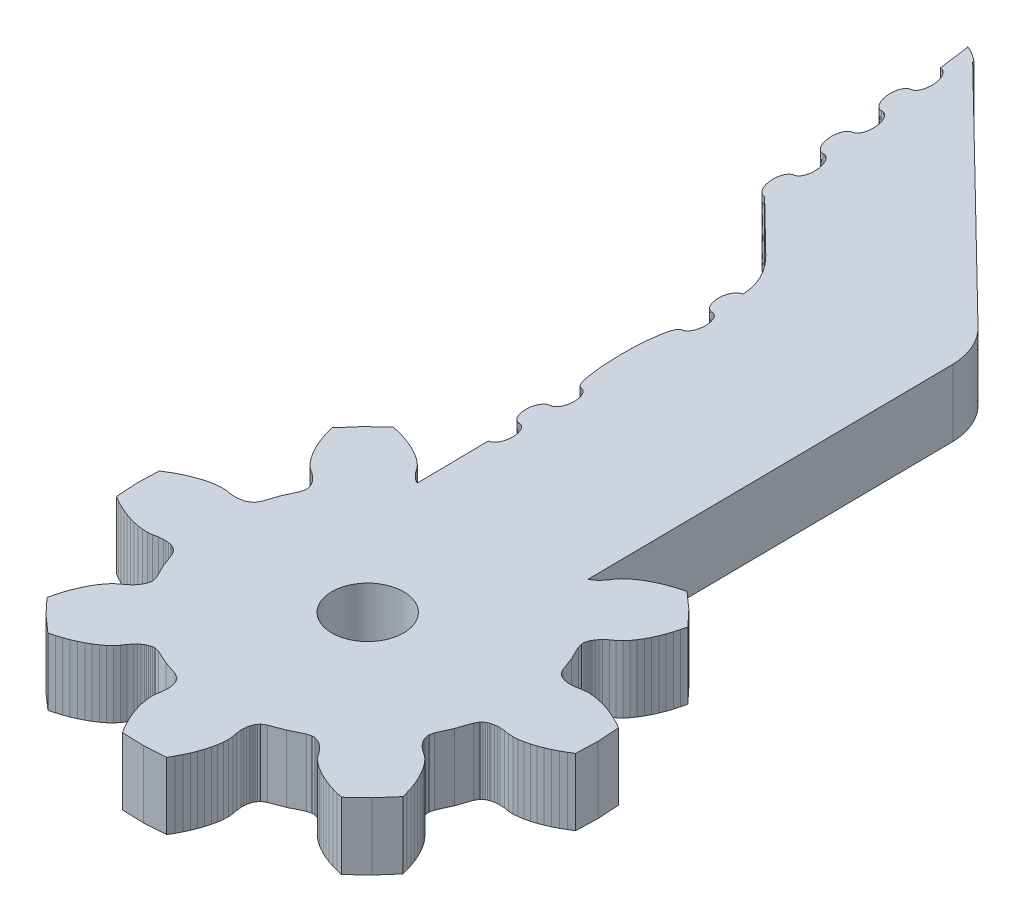
SolidWorks part; units mm, degrees
material "Acrylic (Medium-high impact)"
ref_plane "Front Plane" through (0, 0, 0) normal (0, 0, 1) x (1, 0, 0)
ref_plane "Top Plane" through (0, 0, 0) normal (0, 1, 0) x (1, 0, 0)
ref_plane "Right Plane" through (0, 0, 0) normal (1, 0, 0) x (0, 0, -1)
sketch "Sketch1" plane through (0, 0, 0) normal (0, 1, 0) x (1, 0, 0)
  line L0 (-18.2398, 12.6602) -> (-18.2057, 12.6938)
  line L1 (-18.2057, 12.6938) -> (-18.2497, 16.0706)
  line L2 (-19.267, 30.237) -> (-21.7416, 32.6549)
  line L3 (-22.8499, 42.0906) -> (-23.052, 43.5951)
  line L4 (-23.052, 43.5951) -> (-23.0777, 43.592)
  line L5 (-22.3058, 43.1423) -> (-22.3211, 43.0991)
  line L6 (-22.3211, 43.0991) -> (-11.3066, 32.3367)
  line L7 (-11.3066, 32.3367) -> (-11.3052, 32.3332)
  line L8 (-10.3897, 30.2281) -> (-10.2078, 12.7419)
  line L9 (-10.2078, 12.7419) -> (-10.1981, 12.7564)
  line L10 (-10.1981, 12.7564) -> (-10.1398, 12.7878)
  line L11 (-10.1398, 12.7878) -> (-10.0349, 12.8576)
  line L12 (-10.0349, 12.8576) -> (-9.9419, 12.9344)
  line L13 (-9.9419, 12.9344) -> (-9.858, 13.0164)
  line L14 (-9.858, 13.0164) -> (-9.7113, 13.1935)
  line L15 (-9.7113, 13.1935) -> (-9.5873, 13.3847)
  line L16 (-9.5873, 13.3847) -> (-9.4418, 13.5625)
  line L17 (-9.4418, 13.5625) -> (-9.2671, 13.7214)
  line L18 (-9.2671, 13.7214) -> (-9.0742, 13.868)
  line L19 (-9.0742, 13.868) -> (-8.8661, 14.0037)
  line L20 (-8.8661, 14.0037) -> (-8.6445, 14.1287)
  line L21 (-8.6445, 14.1287) -> (-8.4106, 14.2438)
  line L22 (-8.4106, 14.2438) -> (-8.1654, 14.3483)
  line L23 (-8.1654, 14.3483) -> (-7.9097, 14.4428)
  line L24 (-7.9097, 14.4428) -> (-7.6438, 14.5266)
  line L25 (-7.6438, 14.5266) -> (-7.3688, 14.6001)
  line L26 (-7.3688, 14.6001) -> (-6.5944, 13.9172)
  line L27 (-6.5944, 13.9172) -> (-5.8888, 13.1634)
  line L28 (-5.8888, 13.1634) -> (-5.9533, 12.8854)
  line L29 (-5.9533, 12.8854) -> (-6.0288, 12.6167)
  line L30 (-6.0288, 12.6167) -> (-6.115, 12.3576)
  line L31 (-6.115, 12.3576) -> (-6.2117, 12.1089)
  line L32 (-6.2117, 12.1089) -> (-6.3189, 11.8711)
  line L33 (-6.3189, 11.8711) -> (-6.4368, 11.6453)
  line L34 (-6.4368, 11.6453) -> (-6.5656, 11.4327)
  line L35 (-6.5656, 11.4327) -> (-6.7058, 11.2349)
  line L36 (-6.7058, 11.2349) -> (-6.859, 11.0549)
  line L37 (-6.859, 11.0549) -> (-7.0316, 10.9036)
  line L38 (-7.0316, 10.9036) -> (-7.2185, 10.7734)
  line L39 (-7.2185, 10.7734) -> (-7.3905, 10.621)
  line L40 (-7.3905, 10.621) -> (-7.47, 10.5345)
  line L41 (-7.47, 10.5345) -> (-7.5435, 10.4388)
  line L42 (-7.5435, 10.4388) -> (-7.6098, 10.3316)
  line L43 (-7.6098, 10.3316) -> (-7.6395, 10.2723)
  line L44 (-7.6395, 10.2723) -> (-7.6659, 10.2075)
  line L45 (-7.6659, 10.2075) -> (-7.6884, 10.1356)
  line L46 (-7.6884, 10.1356) -> (-7.7045, 10.0529)
  line L47 (-7.7045, 10.0529) -> (-7.7093, 9.95)
  line L48 (-7.7093, 9.95) -> (-7.6495, 9.7304)
  line L49 (-7.6495, 9.7304) -> (-7.3391, 9.0968)
  line L50 (-7.3391, 9.0968) -> (-7.0906, 8.4366)
  line L51 (-7.0906, 8.4366) -> (-6.9716, 8.2425)
  line L52 (-6.9716, 8.2425) -> (-6.8934, 8.1755)
  line L53 (-6.8934, 8.1755) -> (-6.8222, 8.1306)
  line L54 (-6.8222, 8.1306) -> (-6.7546, 8.0978)
  line L55 (-6.7546, 8.0978) -> (-6.6895, 8.0728)
  line L56 (-6.6895, 8.0728) -> (-6.6259, 8.0539)
  line L57 (-6.6259, 8.0539) -> (-6.5024, 8.0289)
  line L58 (-6.5024, 8.0289) -> (-6.3825, 8.0173)
  line L59 (-6.3825, 8.0173) -> (-6.2653, 8.0158)
  line L60 (-6.2653, 8.0158) -> (-6.0366, 8.0373)
  line L61 (-6.0366, 8.0373) -> (-5.8138, 8.0846)
  line L62 (-5.8138, 8.0846) -> (-5.5857, 8.1071)
  line L63 (-5.5857, 8.1071) -> (-5.3499, 8.0958)
  line L64 (-5.3499, 8.0958) -> (-5.1099, 8.0628)
  line L65 (-5.1099, 8.0628) -> (-4.867, 8.0111)
  line L66 (-4.867, 8.0111) -> (-4.622, 7.9427)
  line L67 (-4.622, 7.9427) -> (-4.3757, 7.8584)
  line L68 (-4.3757, 7.8584) -> (-4.1283, 7.7586)
  line L69 (-4.1283, 7.7586) -> (-3.8809, 7.6443)
  line L70 (-3.8809, 7.6443) -> (-3.6337, 7.5152)
  line L71 (-3.6337, 7.5152) -> (-3.3873, 7.3723)
  line L72 (-3.3873, 7.3723) -> (-3.3217, 6.3409)
  line L73 (-3.3217, 6.3409) -> (-3.355, 5.308)
  line L74 (-3.355, 5.308) -> (-3.5968, 5.1572)
  line L75 (-3.5968, 5.1572) -> (-3.8398, 5.0206)
  line L76 (-3.8398, 5.0206) -> (-4.0836, 4.8983)
  line L77 (-4.0836, 4.8983) -> (-4.3275, 4.7911)
  line L78 (-4.3275, 4.7911) -> (-4.5711, 4.6989)
  line L79 (-4.5711, 4.6989) -> (-4.814, 4.6227)
  line L80 (-4.814, 4.6227) -> (-5.055, 4.5635)
  line L81 (-5.055, 4.5635) -> (-5.2937, 4.523)
  line L82 (-5.2937, 4.523) -> (-5.5291, 4.5043)
  line L83 (-5.5291, 4.5043) -> (-5.758, 4.5197)
  line L84 (-5.758, 4.5197) -> (-5.9821, 4.56)
  line L85 (-5.9821, 4.56) -> (-6.2113, 4.5741)
  line L86 (-6.2113, 4.5741) -> (-6.3285, 4.569)
  line L87 (-6.3285, 4.569) -> (-6.4478, 4.5536)
  line L88 (-6.4478, 4.5536) -> (-6.5705, 4.5248)
  line L89 (-6.5705, 4.5248) -> (-6.6335, 4.5039)
  line L90 (-6.6335, 4.5039) -> (-6.698, 4.4769)
  line L91 (-6.698, 4.4769) -> (-6.7644, 4.4418)
  line L92 (-6.7644, 4.4418) -> (-6.8344, 4.3946)
  line L93 (-6.8344, 4.3946) -> (-6.9102, 4.3254)
  line L94 (-6.9102, 4.3254) -> (-7.023, 4.1278)
  line L95 (-7.023, 4.1278) -> (-7.2507, 3.4599)
  line L96 (-7.2507, 3.4599) -> (-7.5412, 2.8169)
  line L97 (-7.5412, 2.8169) -> (-7.5939, 2.5954)
  line L98 (-7.5939, 2.5954) -> (-7.5859, 2.4927)
  line L99 (-7.5859, 2.4927) -> (-7.5671, 2.4106)
  line L100 (-7.5671, 2.4106) -> (-7.5426, 2.3395)
  line L101 (-7.5426, 2.3395) -> (-7.514, 2.2756)
  line L102 (-7.514, 2.2756) -> (-7.4827, 2.2171)
  line L103 (-7.4827, 2.2171) -> (-7.4129, 2.1121)
  line L104 (-7.4129, 2.1121) -> (-7.3363, 2.0189)
  line L105 (-7.3363, 2.0189) -> (-7.2545, 1.9348)
  line L106 (-7.2545, 1.9348) -> (-7.0776, 1.7879)
  line L107 (-7.0776, 1.7879) -> (-6.8867, 1.6636)
  line L108 (-6.8867, 1.6636) -> (-6.7092, 1.5177)
  line L109 (-6.7092, 1.5177) -> (-6.5508, 1.3428)
  line L110 (-6.5508, 1.3428) -> (-6.4044, 1.1494)
  line L111 (-6.4044, 1.1494) -> (-6.269, 0.941)
  line L112 (-6.269, 0.941) -> (-6.1442, 0.7191)
  line L113 (-6.1442, 0.7191) -> (-6.0294, 0.4849)
  line L114 (-6.0294, 0.4849) -> (-5.9248, 0.2392)
  line L115 (-5.9248, 0.2392) -> (-5.8307, -0.017)
  line L116 (-5.8307, -0.017) -> (-5.7469, -0.2833)
  line L117 (-5.7469, -0.2833) -> (-5.6736, -0.5589)
  line L118 (-5.6736, -0.5589) -> (-6.3551, -1.3347)
  line L119 (-6.3551, -1.3347) -> (-7.1078, -2.0416)
  line L120 (-7.1078, -2.0416) -> (-7.3851, -1.9769)
  line L121 (-7.3851, -1.9769) -> (-7.6535, -1.9013)
  line L122 (-7.6535, -1.9013) -> (-7.9121, -1.8151)
  line L123 (-7.9121, -1.8151) -> (-8.1604, -1.718)
  line L124 (-8.1604, -1.718) -> (-8.3976, -1.6106)
  line L125 (-8.3976, -1.6106) -> (-8.6231, -1.4926)
  line L126 (-8.6231, -1.4926) -> (-8.8354, -1.3636)
  line L127 (-8.8354, -1.3636) -> (-9.0327, -1.2232)
  line L128 (-9.0327, -1.2232) -> (-9.2124, -1.0698)
  line L129 (-9.2124, -1.0698) -> (-9.3634, -0.8967)
  line L130 (-9.3634, -0.8967) -> (-9.4933, -0.7095)
  line L131 (-9.4933, -0.7095) -> (-9.6454, -0.5372)
  line L132 (-9.6454, -0.5372) -> (-9.732, -0.4577)
  line L133 (-9.732, -0.4577) -> (-9.8272, -0.384)
  line L134 (-9.8272, -0.384) -> (-9.9344, -0.3174)
  line L135 (-9.9344, -0.3174) -> (-9.9937, -0.2877)
  line L136 (-9.9937, -0.2877) -> (-10.0583, -0.2612)
  line L137 (-10.0583, -0.2612) -> (-10.13, -0.2389)
  line L138 (-10.13, -0.2389) -> (-10.2126, -0.2227)
  line L139 (-10.2126, -0.2227) -> (-10.3151, -0.2178)
  line L140 (-10.3151, -0.2178) -> (-10.5344, -0.2777)
  line L141 (-10.5344, -0.2777) -> (-11.1668, -0.5889)
  line L142 (-11.1668, -0.5889) -> (-11.826, -0.8376)
  line L143 (-11.826, -0.8376) -> (-12.0198, -0.9568)
  line L144 (-12.0198, -0.9568) -> (-12.0866, -1.0352)
  line L145 (-12.0866, -1.0352) -> (-12.1314, -1.1065)
  line L146 (-12.1314, -1.1065) -> (-12.1642, -1.1741)
  line L147 (-12.1642, -1.1741) -> (-12.189, -1.2395)
  line L148 (-12.189, -1.2395) -> (-12.208, -1.3032)
  line L149 (-12.208, -1.3032) -> (-12.233, -1.4269)
  line L150 (-12.233, -1.4269) -> (-12.2446, -1.547)
  line L151 (-12.2446, -1.547) -> (-12.246, -1.6643)
  line L152 (-12.246, -1.6643) -> (-12.2247, -1.8937)
  line L153 (-12.2247, -1.8937) -> (-12.1774, -2.1167)
  line L154 (-12.1774, -2.1167) -> (-12.1548, -2.3455)
  line L155 (-12.1548, -2.3455) -> (-12.1661, -2.5817)
  line L156 (-12.1661, -2.5817) -> (-12.1991, -2.8219)
  line L157 (-12.1991, -2.8219) -> (-12.2505, -3.0652)
  line L158 (-12.2505, -3.0652) -> (-12.319, -3.3107)
  line L159 (-12.319, -3.3107) -> (-12.4032, -3.5574)
  line L160 (-12.4032, -3.5574) -> (-12.5026, -3.8052)
  line L161 (-12.5026, -3.8052) -> (-12.6169, -4.0532)
  line L162 (-12.6169, -4.0532) -> (-12.7455, -4.3008)
  line L163 (-12.7455, -4.3008) -> (-12.8884, -4.5477)
  line L164 (-12.8884, -4.5477) -> (-13.918, -4.6133)
  line L165 (-13.918, -4.6133) -> (-14.949, -4.5801)
  line L166 (-14.949, -4.5801) -> (-15.0994, -4.3379)
  line L167 (-15.0994, -4.3379) -> (-15.2359, -4.0945)
  line L168 (-15.2359, -4.0945) -> (-15.3577, -3.8502)
  line L169 (-15.3577, -3.8502) -> (-15.4649, -3.6057)
  line L170 (-15.4649, -3.6057) -> (-15.5569, -3.3616)
  line L171 (-15.5569, -3.3616) -> (-15.6328, -3.1185)
  line L172 (-15.6328, -3.1185) -> (-15.692, -2.8768)
  line L173 (-15.692, -2.8768) -> (-15.7324, -2.6377)
  line L174 (-15.7324, -2.6377) -> (-15.751, -2.4021)
  line L175 (-15.751, -2.4021) -> (-15.7358, -2.1727)
  line L176 (-15.7358, -2.1727) -> (-15.6955, -1.9483)
  line L177 (-15.6955, -1.9483) -> (-15.6815, -1.7184)
  line L178 (-15.6815, -1.7184) -> (-15.6866, -1.601)
  line L179 (-15.6866, -1.601) -> (-15.702, -1.4815)
  line L180 (-15.702, -1.4815) -> (-15.7306, -1.3587)
  line L181 (-15.7306, -1.3587) -> (-15.7516, -1.2956)
  line L182 (-15.7516, -1.2956) -> (-15.7786, -1.2311)
  line L183 (-15.7786, -1.2311) -> (-15.8135, -1.1643)
  line L184 (-15.8135, -1.1643) -> (-15.8604, -1.0945)
  line L185 (-15.8604, -1.0945) -> (-15.9296, -1.0183)
  line L186 (-15.9296, -1.0183) -> (-16.127, -0.9054)
  line L187 (-16.127, -0.9054) -> (-16.7936, -0.6772)
  line L188 (-16.7936, -0.6772) -> (-17.4355, -0.3862)
  line L189 (-17.4355, -0.3862) -> (-17.6566, -0.3334)
  line L190 (-17.6566, -0.3334) -> (-17.7591, -0.3414)
  line L191 (-17.7591, -0.3414) -> (-17.841, -0.3601)
  line L192 (-17.841, -0.3601) -> (-17.9121, -0.3849)
  line L193 (-17.9121, -0.3849) -> (-17.9757, -0.4134)
  line L194 (-17.9757, -0.4134) -> (-18.0342, -0.445)
  line L195 (-18.0342, -0.445) -> (-18.1391, -0.5148)
  line L196 (-18.1391, -0.5148) -> (-18.232, -0.5914)
  line L197 (-18.232, -0.5914) -> (-18.316, -0.6736)
  line L198 (-18.316, -0.6736) -> (-18.4627, -0.8507)
  line L199 (-18.4627, -0.8507) -> (-18.5867, -1.0419)
  line L200 (-18.5867, -1.0419) -> (-18.7322, -1.2195)
  line L201 (-18.7322, -1.2195) -> (-18.907, -1.3786)
  line L202 (-18.907, -1.3786) -> (-19.0998, -1.525)
  line L203 (-19.0998, -1.525) -> (-19.3079, -1.6608)
  line L204 (-19.3079, -1.6608) -> (-19.5296, -1.786)
  line L205 (-19.5296, -1.786) -> (-19.7634, -1.9008)
  line L206 (-19.7634, -1.9008) -> (-20.0084, -2.0055)
  line L207 (-20.0084, -2.0055) -> (-20.2643, -2.0998)
  line L208 (-20.2643, -2.0998) -> (-20.5302, -2.1838)
  line L209 (-20.5302, -2.1838) -> (-20.8053, -2.2573)
  line L210 (-20.8053, -2.2573) -> (-21.5796, -1.5744)
  line L211 (-21.5796, -1.5744) -> (-22.2852, -0.8205)
  line L212 (-22.2852, -0.8205) -> (-22.2207, -0.5426)
  line L213 (-22.2207, -0.5426) -> (-22.1452, -0.2737)
  line L214 (-22.1452, -0.2737) -> (-22.059, -0.0148)
  line L215 (-22.059, -0.0148) -> (-21.9623, 0.2341)
  line L216 (-21.9623, 0.2341) -> (-21.8551, 0.4718)
  line L217 (-21.8551, 0.4718) -> (-21.7372, 0.6977)
  line L218 (-21.7372, 0.6977) -> (-21.6084, 0.9103)
  line L219 (-21.6084, 0.9103) -> (-21.4683, 1.1081)
  line L220 (-21.4683, 1.1081) -> (-21.3152, 1.2881)
  line L221 (-21.3152, 1.2881) -> (-21.1423, 1.4392)
  line L222 (-21.1423, 1.4392) -> (-20.9556, 1.5694)
  line L223 (-20.9556, 1.5694) -> (-20.7834, 1.7218)
  line L224 (-20.7834, 1.7218) -> (-20.7042, 1.8085)
  line L225 (-20.7042, 1.8085) -> (-20.6305, 1.904)
  line L226 (-20.6305, 1.904) -> (-20.5642, 2.0112)
  line L227 (-20.5642, 2.0112) -> (-20.5345, 2.0706)
  line L228 (-20.5345, 2.0706) -> (-20.5081, 2.1353)
  line L229 (-20.5081, 2.1353) -> (-20.4856, 2.2072)
  line L230 (-20.4856, 2.2072) -> (-20.4695, 2.2899)
  line L231 (-20.4695, 2.2899) -> (-20.4648, 2.3928)
  line L232 (-20.4648, 2.3928) -> (-20.5246, 2.6125)
  line L233 (-20.5246, 2.6125) -> (-20.8349, 3.246)
  line L234 (-20.8349, 3.246) -> (-21.0835, 3.9064)
  line L235 (-21.0835, 3.9064) -> (-21.2024, 4.1005)
  line L236 (-21.2024, 4.1005) -> (-21.2805, 4.1674)
  line L237 (-21.2805, 4.1674) -> (-21.3517, 4.2122)
  line L238 (-21.3517, 4.2122) -> (-21.4192, 4.2452)
  line L239 (-21.4192, 4.2452) -> (-21.4846, 4.27)
  line L240 (-21.4846, 4.27) -> (-21.5481, 4.2891)
  line L241 (-21.5481, 4.2891) -> (-21.6715, 4.3139)
  line L242 (-21.6715, 4.3139) -> (-21.7913, 4.3257)
  line L243 (-21.7913, 4.3257) -> (-21.9087, 4.3272)
  line L244 (-21.9087, 4.3272) -> (-22.1374, 4.3057)
  line L245 (-22.1374, 4.3057) -> (-22.3602, 4.2584)
  line L246 (-22.3602, 4.2584) -> (-22.5885, 4.2357)
  line L247 (-22.5885, 4.2357) -> (-22.8242, 4.2472)
  line L248 (-22.8242, 4.2472) -> (-23.0641, 4.2802)
  line L249 (-23.0641, 4.2802) -> (-23.307, 4.3317)
  line L250 (-23.307, 4.3317) -> (-23.552, 4.4003)
  line L251 (-23.552, 4.4003) -> (-23.7983, 4.4846)
  line L252 (-23.7983, 4.4846) -> (-24.0457, 4.5843)
  line L253 (-24.0457, 4.5843) -> (-24.2931, 4.6987)
  line L254 (-24.2931, 4.6987) -> (-24.5403, 4.8276)
  line L255 (-24.5403, 4.8276) -> (-24.7868, 4.9707)
  line L256 (-24.7868, 4.9707) -> (-24.8523, 6.002)
  line L257 (-24.8523, 6.002) -> (-24.819, 7.035)
  line L258 (-24.819, 7.035) -> (-24.5773, 7.1858)
  line L259 (-24.5773, 7.1858) -> (-24.3344, 7.3224)
  line L260 (-24.3344, 7.3224) -> (-24.0904, 7.4445)
  line L261 (-24.0904, 7.4445) -> (-23.8465, 7.5519)
  line L262 (-23.8465, 7.5519) -> (-23.6027, 7.6441)
  line L263 (-23.6027, 7.6441) -> (-23.3601, 7.7201)
  line L264 (-23.3601, 7.7201) -> (-23.119, 7.7794)
  line L265 (-23.119, 7.7794) -> (-22.8803, 7.8199)
  line L266 (-22.8803, 7.8199) -> (-22.6449, 7.8386)
  line L267 (-22.6449, 7.8386) -> (-22.416, 7.8234)
  line L268 (-22.416, 7.8234) -> (-22.1919, 7.7828)
  line L269 (-22.1919, 7.7828) -> (-21.9627, 7.7687)
  line L270 (-21.9627, 7.7687) -> (-21.8455, 7.7738)
  line L271 (-21.8455, 7.7738) -> (-21.726, 7.7892)
  line L272 (-21.726, 7.7892) -> (-21.6034, 7.818)
  line L273 (-21.6034, 7.818) -> (-21.5405, 7.8391)
  line L274 (-21.5405, 7.8391) -> (-21.4761, 7.8662)
  line L275 (-21.4761, 7.8662) -> (-21.4096, 7.9012)
  line L276 (-21.4096, 7.9012) -> (-21.3398, 7.9482)
  line L277 (-21.3398, 7.9482) -> (-21.2638, 8.0175)
  line L278 (-21.2638, 8.0175) -> (-21.151, 8.2152)
  line L279 (-21.151, 8.2152) -> (-20.9233, 8.8831)
  line L280 (-20.9233, 8.8831) -> (-20.6329, 9.5261)
  line L281 (-20.6329, 9.5261) -> (-20.5802, 9.7476)
  line L282 (-20.5802, 9.7476) -> (-20.5881, 9.85)
  line L283 (-20.5881, 9.85) -> (-20.6068, 9.9322)
  line L284 (-20.6068, 9.9322) -> (-20.6314, 10.0034)
  line L285 (-20.6314, 10.0034) -> (-20.66, 10.0672)
  line L286 (-20.66, 10.0672) -> (-20.6915, 10.1258)
  line L287 (-20.6915, 10.1258) -> (-20.7611, 10.2309)
  line L288 (-20.7611, 10.2309) -> (-20.8377, 10.3239)
  line L289 (-20.8377, 10.3239) -> (-20.9195, 10.4082)
  line L290 (-20.9195, 10.4082) -> (-21.0965, 10.5551)
  line L291 (-21.0965, 10.5551) -> (-21.2873, 10.6792)
  line L292 (-21.2873, 10.6792) -> (-21.4646, 10.8251)
  line L293 (-21.4646, 10.8251) -> (-21.6235, 11)
  line L294 (-21.6235, 11) -> (-21.7696, 11.1934)
  line L295 (-21.7696, 11.1934) -> (-21.9051, 11.4018)
  line L296 (-21.9051, 11.4018) -> (-22.0298, 11.6237)
  line L297 (-22.0298, 11.6237) -> (-22.1445, 11.8581)
  line L298 (-22.1445, 11.8581) -> (-22.2492, 12.1037)
  line L299 (-22.2492, 12.1037) -> (-22.3433, 12.36)
  line L300 (-22.3433, 12.36) -> (-22.4272, 12.6261)
  line L301 (-22.4272, 12.6261) -> (-22.5006, 12.9019)
  line L302 (-22.5006, 12.9019) -> (-21.8187, 13.6777)
  line L303 (-21.8187, 13.6777) -> (-21.0662, 14.3846)
  line L304 (-21.0662, 14.3846) -> (-20.7889, 14.32)
  line L305 (-20.7889, 14.32) -> (-20.5205, 14.2443)
  line L306 (-20.5205, 14.2443) -> (-20.262, 14.1579)
  line L307 (-20.262, 14.1579) -> (-20.0136, 14.0611)
  line L308 (-20.0136, 14.0611) -> (-19.7762, 13.9536)
  line L309 (-19.7762, 13.9536) -> (-19.551, 13.8355)
  line L310 (-19.551, 13.8355) -> (-19.3387, 13.7066)
  line L311 (-19.3387, 13.7066) -> (-19.1413, 13.5661)
  line L312 (-19.1413, 13.5661) -> (-18.9616, 13.4127)
  line L313 (-18.9616, 13.4127) -> (-18.8106, 13.2397)
  line L314 (-18.8106, 13.2397) -> (-18.6805, 13.0525)
  line L315 (-18.6805, 13.0525) -> (-18.5284, 12.88)
  line L316 (-18.5284, 12.88) -> (-18.442, 12.8005)
  line L317 (-18.442, 12.8005) -> (-18.3468, 12.7269)
  line L318 (-18.3468, 12.7269) -> (-18.2398, 12.6602)
  line L319 (-15.5718, 6.1716) -> (-12.5769, 6.1714) construction
  circle A0 centre (-14.0743, 6.1715) radius 1.7
  spline S0 degree 3 poles (-18.2497, 16.0706) (-18.0221, 16.0737) (-17.8375, 16.4031) (-17.8375, 16.8059) knots 2 2 2 2 3 3 3 3
  spline S1 degree 3 poles (-17.8375, 16.8059) (-17.8375, 17.209) (-18.0221, 17.5331) (-18.2497, 17.5298) knots 3 3 3 3 4 4 4 4
  spline S2 degree 3 poles (-18.2497, 17.5298) (-18.4776, 17.5267) (-18.6621, 17.8508) (-18.6621, 18.2537) knots 4 4 4 4 5 5 5 5
  spline S3 degree 3 poles (-18.6621, 18.2537) (-18.6621, 18.6567) (-18.4776, 18.986) (-18.2497, 18.9892) knots 5 5 5 5 6 6 6 6
  spline S4 degree 3 poles (-18.2497, 18.9892) (-18.0221, 18.9925) (-17.8375, 19.3216) (-17.8375, 19.7248) knots 6 6 6 6 7 7 7 7
  spline S5 degree 3 poles (-17.8375, 19.7248) (-17.8375, 20.1276) (-18.0221, 20.4517) (-18.2497, 20.4487) knots 7 7 7 7 8 8 8 8
  spline S6 degree 3 poles (-18.2497, 20.4487) (-18.4776, 20.4383) (-18.6621, 21.4953) (-18.6621, 22.8094) knots 8 8 8 8 9 9 9 9
  spline S7 degree 3 poles (-18.6621, 22.8094) (-18.6621, 24.1237) (-18.4776, 25.1974) (-18.2497, 25.2079) knots 9 9 9 9 10 10 10 10
  spline S8 degree 3 poles (-18.2497, 25.2079) (-18.0223, 25.2112) (-17.8377, 25.5403) (-17.8377, 25.9434) knots 10 10 10 10 11 11 11 11
  spline S9 degree 3 poles (-17.8377, 25.9434) (-17.8377, 26.3464) (-18.0223, 26.6704) (-18.2499, 26.6671) knots 11 11 11 11 12 12 12 12
  spline S10 degree 3 poles (-18.2499, 26.6671) (-18.4776, 26.6641) (-18.6621, 26.9881) (-18.6621, 27.3911) knots 12 12 12 12 13 13 13 13
  spline S11 degree 3 poles (-18.6621, 27.3911) (-18.6621, 27.794) (-18.4776, 28.1233) (-18.2499, 28.1264) knots 13 13 13 13 14 14 14 14
  spline S12 degree 3 poles (-18.2499, 28.1264) (-18.2599, 28.9221) (-18.6985, 29.6812) (-19.267, 30.237) knots 14 14 14 14 15 15 15 15
  spline S13 degree 3 poles (-21.7416, 32.6549) (-21.9681, 32.6317) (-22.193, 32.9648) (-22.2441, 33.3991) knots 16 16 16 16 17 17 17 17
  spline S14 degree 3 poles (-22.2441, 33.3991) (-22.2952, 33.8335) (-22.1528, 34.2041) (-21.9263, 34.2274) knots 17 17 17 17 18 18 18 18
  spline S15 degree 3 poles (-21.9263, 34.2274) (-21.6997, 34.2508) (-21.5574, 34.6216) (-21.6084, 35.0558) knots 18 18 18 18 19 19 19 19
  spline S16 degree 3 poles (-21.6084, 35.0558) (-21.6595, 35.4901) (-21.8844, 35.8232) (-22.111, 35.8) knots 19 19 19 19 20 20 20 20
  spline S17 degree 3 poles (-22.111, 35.8) (-22.3374, 35.777) (-22.5625, 36.11) (-22.6134, 36.5444) knots 20 20 20 20 21 21 21 21
  spline S18 degree 3 poles (-22.6134, 36.5444) (-22.6644, 36.9786) (-22.5223, 37.3495) (-22.2956, 37.3728) knots 21 21 21 21 22 22 22 22
  spline S19 degree 3 poles (-22.2956, 37.3728) (-22.0692, 37.396) (-21.9268, 37.7669) (-21.9779, 38.201) knots 22 22 22 22 23 23 23 23
  spline S20 degree 3 poles (-21.9779, 38.201) (-22.029, 38.6354) (-22.2539, 38.9687) (-22.4805, 38.9452) knots 23 23 23 23 24 24 24 24
  spline S21 degree 3 poles (-22.4805, 38.9452) (-22.7068, 38.9222) (-22.932, 39.2553) (-22.9828, 39.6897) knots 24 24 24 24 25 25 25 25
  spline S22 degree 3 poles (-22.9828, 39.6897) (-23.0339, 40.124) (-22.8917, 40.4947) (-22.665, 40.5179) knots 25 25 25 25 26 26 26 26
  spline S23 degree 3 poles (-22.665, 40.5179) (-22.4386, 40.5413) (-22.2963, 40.9122) (-22.3472, 41.3463) knots 26 26 26 26 27 27 27 27
  spline S24 degree 3 poles (-22.3472, 41.3463) (-22.3984, 41.7806) (-22.6232, 42.1137) (-22.8499, 42.0906) knots 27 27 27 27 28 28 28 28
  spline S25 degree 3 poles (-23.0777, 43.592) (-23.0786, 43.659) (-22.5438, 43.3751) (-22.3058, 43.1423) knots 30 30 30 30 31 31 31 31
  spline S26 degree 3 poles (-11.3052, 32.3332) (-10.7335, 31.7808) (-10.404, 31.0237) (-10.3897, 30.2281) knots 34 34 34 34 35 35 35 35
  dimension "D1" = 3.4
extrude "Boss-Extrude1" add sketch "Sketch1" along normal blind 3.175
